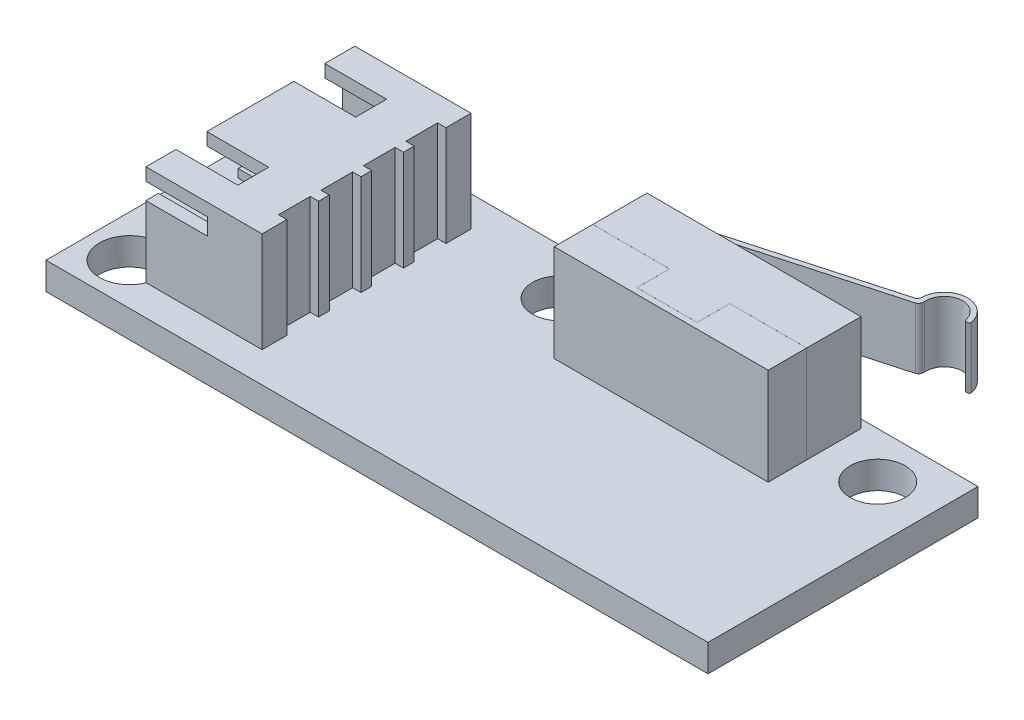
SolidWorks part; units mm, degrees
ref_plane "Front Plane" through (0, 0, 0) normal (0, 0, 1) x (1, 0, 0)
ref_plane "Top Plane" through (0, 0, 0) normal (0, 1, 0) x (1, 0, 0)
ref_plane "Right Plane" through (0, 0, 0) normal (1, 0, 0) x (0, 0, -1)
sketch "Sketch1" plane through (0, 0, 0) normal (0, 1, 0) x (1, 0, 0)
  line L1 (-19.8, 8.075) -> (19.8, 8.075)
  line L2 (-19.8, 8.075) -> (-19.8, -8.075)
  line L3 (-19.8, -8.075) -> (19.8, -8.075)
  line L4 (19.8, 8.075) -> (19.8, -8.075)
  circle A0 centre (-17.3, 5.575) radius 1.8
  circle A1 centre (-17.3, -5.575) radius 1.8
  circle A2 centre (-2.45, 5.325) radius 1.65
  circle A3 centre (16.55, 5.325) radius 1.65
  dimension "D5" = 3.3
  dimension "D6" = 3.3
  dimension "D7" = 3.6
  dimension "D8" = 3.6
  dimension "D1" = 39.6
  dimension "D2" = 16.15
  dimension "D3" = 19.8
  dimension "D4" = 8.075
  dimension "D9" = 2.5
  dimension "D10" = 2.5
  dimension "D11" = 2.5
  dimension "D12" = 2.5
  dimension "D13" = 2.75
  dimension "D14" = 2.75
  dimension "D15" = 3.25
  dimension "D16" = 19
extrude "Boss-Extrude1" add sketch "Sketch1" along normal blind 1.63
sketch "Sketch2" plane through (0, 1.63, 0) normal (0, 1, 0) x (1, 0, 0)
  line L0 (19.8, 8.075) -> (-19.8, 8.075) construction
  line L1 (-8.7, 6.25) -> (-15.65, 6.25)
  line L2 (-8.7, 6.25) -> (-8.7, -6.25)
  line L3 (-8.7, -6.25) -> (-15.65, -6.25)
  line L4 (-15.65, 6.25) -> (-15.65, -6.25)
  line L5 (-19.8, -8.075) -> (19.8, -8.075) construction
  line L6 (-19.8, 8.075) -> (-19.8, -8.075) construction
  dimension "D1" = 6.95
  dimension "D2" = 12.5
  dimension "D3" = 1.825
  dimension "D4" = 1.825
  dimension "D5" = 4.15
extrude "Boss-Extrude2" add sketch "Sketch2" along normal blind 6
sketch "Sketch3" plane through (-15.65, 0, 0) normal (-1, 0, 0) x (0, 0, 1)
  line L0 (-6.25, 7.63) -> (-6.25, 1.63) construction
  line L1 (-5.5, 6.88) -> (5.5, 6.88)
  line L2 (-5.5, 6.88) -> (-5.5, 2.38)
  line L3 (-5.5, 2.38) -> (5.5, 2.38)
  line L4 (5.5, 6.88) -> (5.5, 2.38)
  line L5 (-6.25, 7.63) -> (6.25, 7.63) construction
  line L6 (6.25, 7.63) -> (6.25, 1.63) construction
  line L7 (-4.8556, 1.63) -> (4.8556, 1.63) construction
  dimension "D1" = 0.75
  dimension "D2" = 0.75
  dimension "D3" = 0.75
  dimension "D4" = 0.75
extrude "Cut-Extrude1" cut sketch "Sketch3" against normal blind 4.65
sketch "Sketch4" plane through (-15.65, 0, 0) normal (-1, 0, 0) x (0, 0, 1)
  line L0 (-6.25, 7.63) -> (6.25, 7.63) construction
  line L1 (-4.45, 7.63) -> (-2.6, 7.63)
  line L2 (-4.45, 7.63) -> (-4.45, 6.88)
  line L3 (-4.45, 6.88) -> (-2.6, 6.88)
  line L4 (-2.6, 7.63) -> (-2.6, 6.88)
  line L5 (5.5, 6.88) -> (-5.5, 6.88) construction
  line L6 (-6.25, 7.63) -> (-6.25, 1.63) construction
  line L7 (-5.5, 6.88) -> (-6.25, 6.88)
  line L8 (-5.5, 6.88) -> (-5.5, 5.88)
  line L9 (-5.5, 5.88) -> (-6.25, 5.88)
  line L10 (-6.25, 6.88) -> (-6.25, 5.88)
  line L11 (6.25, 7.63) -> (6.25, 1.63) construction
  line L12 (5.5, 6.88) -> (6.25, 6.88)
  line L13 (5.5, 6.88) -> (5.5, 5.88)
  line L14 (5.5, 5.88) -> (6.25, 5.88)
  line L15 (6.25, 6.88) -> (6.25, 5.88)
  line L17 (4.45, 6.88) -> (2.6, 6.88)
  line L18 (4.45, 6.88) -> (4.45, 7.63)
  line L19 (4.45, 7.63) -> (2.6, 7.63)
  line L20 (2.6, 6.88) -> (2.6, 7.63)
  dimension "D1" = 1
  dimension "D2" = 1
  dimension "D3" = 1.85
  dimension "D4" = 1.85
  dimension "D5" = 1.8
  dimension "D6" = 1.8
extrude "Cut-Extrude2" cut sketch "Sketch4" against normal blind 3.7
sketch "Sketch5" plane through (0, 7.63, 0) normal (0, 1, 0) x (1, 0, 0)
  line L0 (-8.7, -6.25) -> (-8.7, 6.25) construction
  line L1 (-8.7, 4.75) -> (-9.2, 4.75)
  line L2 (-8.7, 4.75) -> (-8.7, 2.85)
  line L3 (-8.7, 2.85) -> (-9.2, 2.85)
  line L4 (-9.2, 4.75) -> (-9.2, 2.85)
  line L5 (-8.7, 6.25) -> (-15.6314, 6.25) construction
  line L6 (-8.7, 2.21) -> (-8.7, 0.31)
  line L7 (-8.7, 2.21) -> (-9.2, 2.21)
  line L8 (-9.2, 2.21) -> (-9.2, 0.31)
  line L9 (-8.7, 0.31) -> (-9.2, 0.31)
  line L10 (-8.7, -0.33) -> (-8.7, -2.23)
  line L11 (-8.7, -0.33) -> (-9.2, -0.33)
  line L12 (-9.2, -0.33) -> (-9.2, -2.23)
  line L13 (-8.7, -2.23) -> (-9.2, -2.23)
  line L14 (-8.7, -2.87) -> (-8.7, -4.77)
  line L15 (-8.7, -2.87) -> (-9.2, -2.87)
  line L16 (-9.2, -2.87) -> (-9.2, -4.77)
  line L17 (-8.7, -4.77) -> (-9.2, -4.77)
  dimension "D1" = 1.9
  dimension "D2" = 1.5
  dimension "D3" = 0.5
  dimension "D4" = 4
extrude "Cut-Extrude3" cut sketch "Sketch5" against normal up to surface (6 mm away) up to face at (-14.4802, 1.63, 0)
sketch "Sketch6" plane through (-11, 0, 0) normal (-1, 0, 0) x (0, 0, 1)
  line L0 (-4.45, 6.88) -> (-6.25, 6.88) construction
  line L1 (-4.1, 5.63) -> (-3.5, 5.63)
  line L2 (-4.1, 5.63) -> (-4.1, 5.13)
  line L3 (-4.1, 5.13) -> (-3.5, 5.13)
  line L4 (-3.5, 5.63) -> (-3.5, 5.13)
  line L5 (-5.5, 6.88) -> (-5.5, 2.38) construction
  line L6 (-1.56, 5.63) -> (-1.56, 5.13)
  line L7 (-1.56, 5.63) -> (-0.96, 5.63)
  line L8 (-0.96, 5.63) -> (-0.96, 5.13)
  line L9 (-1.56, 5.13) -> (-0.96, 5.13)
  line L10 (0.98, 5.63) -> (0.98, 5.13)
  line L11 (0.98, 5.63) -> (1.58, 5.63)
  line L12 (1.58, 5.63) -> (1.58, 5.13)
  line L13 (0.98, 5.13) -> (1.58, 5.13)
  line L14 (3.52, 5.63) -> (3.52, 5.13)
  line L15 (3.52, 5.63) -> (4.12, 5.63)
  line L16 (4.12, 5.63) -> (4.12, 5.13)
  line L17 (3.52, 5.13) -> (4.12, 5.13)
  dimension "D1" = 0.6
  dimension "D2" = 0.5
  dimension "D3" = 1.25
  dimension "D4" = 1.4
  dimension "D5" = 4
extrude "Boss-Extrude3" add sketch "Sketch6" along normal blind 3.9
chamfer "Chamfer1" distance 0.1 angle 45 16 edges at (-14.9, 5.38, 4.12) (-14.9, 5.13, 3.82) (-14.9, 5.38, 3.52) (-14.9, 5.63, 3.82) (-14.9, 5.38, 1.58) (-14.9, 5.13, 1.28) (-14.9, 5.38, 0.98) (-14.9, 5.63, 1.28) (-14.9, 5.38, -0.96) (-14.9, 5.13, -1.26) (-14.9, 5.38, -1.56) (-14.9, 5.63, -1.26) (-14.9, 5.63, -3.8) (-14.9, 5.38, -3.5) (-14.9, 5.13, -3.8) (-14.9, 5.38, -4.1)
sketch "Sketch7" plane through (0, 1.63, 0) normal (0, 1, 0) x (1, 0, 0)
  line L0 (19.8, -8.075) -> (19.8, 8.075) construction
  line L1 (0.5, 7.575) -> (13.3, 7.575)
  line L2 (0.5, 7.575) -> (0.5, 4.325)
  line L4 (13.3, 7.575) -> (13.3, 4.325)
  line L5 (0.5, 4.325) -> (5.1, 4.325)
  line L6 (5.1, 4.325) -> (5.1, 2.375)
  line L7 (5.1, 2.375) -> (8.7, 2.375)
  line L8 (8.7, 2.375) -> (8.7, 4.325)
  line L9 (8.7, 4.325) -> (13.3, 4.325)
  line L10 (19.8, 8.075) -> (-19.8, 8.075) construction
  dimension "D1" = 12.8
  dimension "D2" = 6.5
  dimension "D3" = 3.6
  dimension "D4" = 4.6
  dimension "D5" = 3.25
  dimension "D6" = 3.25
  dimension "D7" = 0.5
  dimension "D8" = 1.95
extrude "Boss-Extrude4" add sketch "Sketch7" along normal blind 5.8
sketch "Sketch8" plane through (0, 1.63, 0) normal (0, 1, 0) x (1, 0, 0)
  line L0 (0.5, 4.324) -> (0.5, 2.025)
  line L1 (0.5, 2.025) -> (13.3, 2.025)
  line L2 (13.3, 2.025) -> (13.3, 4.324)
  line L3 (13.3, 4.324) -> (8.701, 4.324)
  line L4 (8.701, 4.324) -> (8.701, 2.374)
  line L5 (8.701, 2.374) -> (5.099, 2.374)
  line L6 (5.099, 2.374) -> (5.099, 4.324)
  line L7 (5.099, 4.324) -> (0.5, 4.324)
  line L8 (0.5, 4.325) -> (5.1, 4.325) construction
  line L9 (0.5, 4.325) -> (5.1, 4.325) construction
  line L10 (5.1, 4.325) -> (5.1, 2.375) construction
  line L11 (5.1, 2.375) -> (8.7, 2.375) construction
  line L12 (8.7, 2.375) -> (8.7, 4.325) construction
  line L13 (8.7, 4.325) -> (13.3, 4.325) construction
  dimension "D1" = 2.3
  dimension "D2" = 0.001
  dimension "D3" = 0.001
  dimension "D4" = 0.001
  dimension "D5" = 0.001
  dimension "D6" = 0.001
extrude "Boss-Extrude5" add sketch "Sketch8" along normal blind 5.8
sketch "Sketch9" plane through (0, 0, -7.575) normal (0, 0, -1) x (-1, 0, 0)
  line L0 (-13.3, 7.43) -> (-0.5, 7.43) construction
  line L1 (-4.3, 5.93) -> (-5.3, 5.93)
  line L2 (-4.3, 5.93) -> (-4.3, 3.13)
  line L3 (-4.3, 3.13) -> (-5.3, 3.13)
  line L4 (-5.3, 5.93) -> (-5.3, 3.13)
  line L5 (-13.3, 1.63) -> (-0.5, 1.63) construction
  line L6 (-0.5, 7.43) -> (-0.5, 1.63) construction
  dimension "D1" = 1
  dimension "D2" = 2.8
  dimension "D3" = 1.5
  dimension "D4" = 1.5
  dimension "D5" = 3.8
extrude "Boss-Extrude6" add sketch "Sketch9" along normal blind 0.75
fillet "Fillet1" radius 0.25 2 edges at (4.3, 4.53, -8.325) (5.3, 4.53, -8.325)
ref_plane "Plane1" through (0, 2.88, 0) normal (0, 1, 0) x (1, 0, 0)
sketch "Sketch10" plane through (0, 2.88, 0) normal (0, 1, 0) x (1, 0, 0)
  line L0 (1.65, 7.575) -> (1.65, 7.6851)
  line L1 (13.3, 7.575) -> (0.5, 7.575) construction
  line L2 (1.833, 7.9259) -> (13.0349, 11.0441)
  line L3 (0.5, 7.575) -> (0.5, 4.325) construction
  line L4 (1.65, 7.575) -> (1.95, 7.575)
  line L5 (13.3, 7.575) -> (0.5, 7.575) construction
  line L6 (1.95, 7.575) -> (1.95, 7.6091)
  line L7 (1.9866, 7.6573) -> (13.3219, 10.8126)
  line L8 (13.5204, 11.1543) -> (13.5204, 11.1543)
  line L9 (13.5204, 11.1543) -> (13.5204, 11.1543)
  line L10 (13.5204, 11.1543) -> (13.5204, 11.1543)
  line L11 (13.5204, 11.1543) -> (13.5204, 11.1543)
  line L12 (13.5204, 11.1543) -> (13.5204, 11.1543)
  line L13 (13.5204, 11.1543) -> (13.5027, 11.0206)
  line L14 (15.8069, 11.3584) -> (15.9067, 11.3686)
  line L15 (1.95, 7.6471) -> (13.481, 10.8569) construction
  line L16 (1.65, 7.875) -> (13.2243, 11.0968) construction
  line L17 (1.65, 7.575) -> (1.65, 7.875) construction
  line L18 (1.95, 7.575) -> (1.95, 7.6471) construction
  arc A0 (13.2177, 11.2778) -> (15.9951, 11.4858) centre (14.6172, 11.2379) cw
  arc A1 (13.5204, 11.1543) -> (15.6985, 11.4396) centre (14.6172, 11.2379) cw
  arc A2 (13.3219, 10.8126) -> (13.5027, 11.0206) centre (13.2548, 11.0534) ccw
  arc A3 (13.2243, 11.0968) -> (16.01, 11.379) centre (14.6172, 11.2379) cw construction
  arc A4 (13.0349, 11.0441) -> (13.2177, 11.2778) centre (12.9678, 11.2849) ccw
  arc A5 (1.833, 7.9259) -> (1.65, 7.6851) centre (1.9, 7.6851) ccw
  arc A6 (15.9067, 11.3686) -> (15.9951, 11.4858) centre (15.8966, 11.4681) ccw
  arc A7 (13.5204, 11.1543) -> (15.7116, 11.3488) centre (14.6172, 11.2379) cw construction
  arc A8 (15.8069, 11.3584) -> (15.6985, 11.4396) centre (15.7968, 11.4579) cw
  arc A9 (1.9866, 7.6573) -> (1.95, 7.6091) centre (2, 7.6091) ccw
  point P29 (13.2243, 11.0968)
  dimension "D7" = 0.25
  dimension "D2" = 0.1
  dimension "D3" = 0.05
  dimension "D1" = 0.3
  dimension "D4" = 1.15
  dimension "D5" = 0.3
  dimension "D6" = 0.3
extrude "Boss-Extrude7" add sketch "Sketch10" along normal blind 3.65 contours A9 L7 A2 L13 A1 A8 L14 A6 A0 A4 L2 A5 L0 L4 L6
sketch "Sketch11" plane through (1.1236, 0, -7.7285) normal (0.2682, 0, 0.9634) x (0.9634, 0, -0.2682)
  line L0 (0.466, 6.53) -> (0.466, 2.88) construction
  line L1 (0.466, 5.13) -> (8.136, 5.13)
  line L2 (0.466, 5.13) -> (0.466, 4.28)
  line L3 (0.466, 4.28) -> (8.136, 4.28)
  line L5 (0.7364, 6.53) -> (12.3642, 6.53) construction
  arc A2 (8.136, 5.13) -> (8.136, 4.28) centre (8.136, 4.705) cw
  dimension "D1" = 0.85
  dimension "D2" = 1.4
extrude "Cut-Extrude4" cut sketch "Sketch11" along normal blind 0.3
